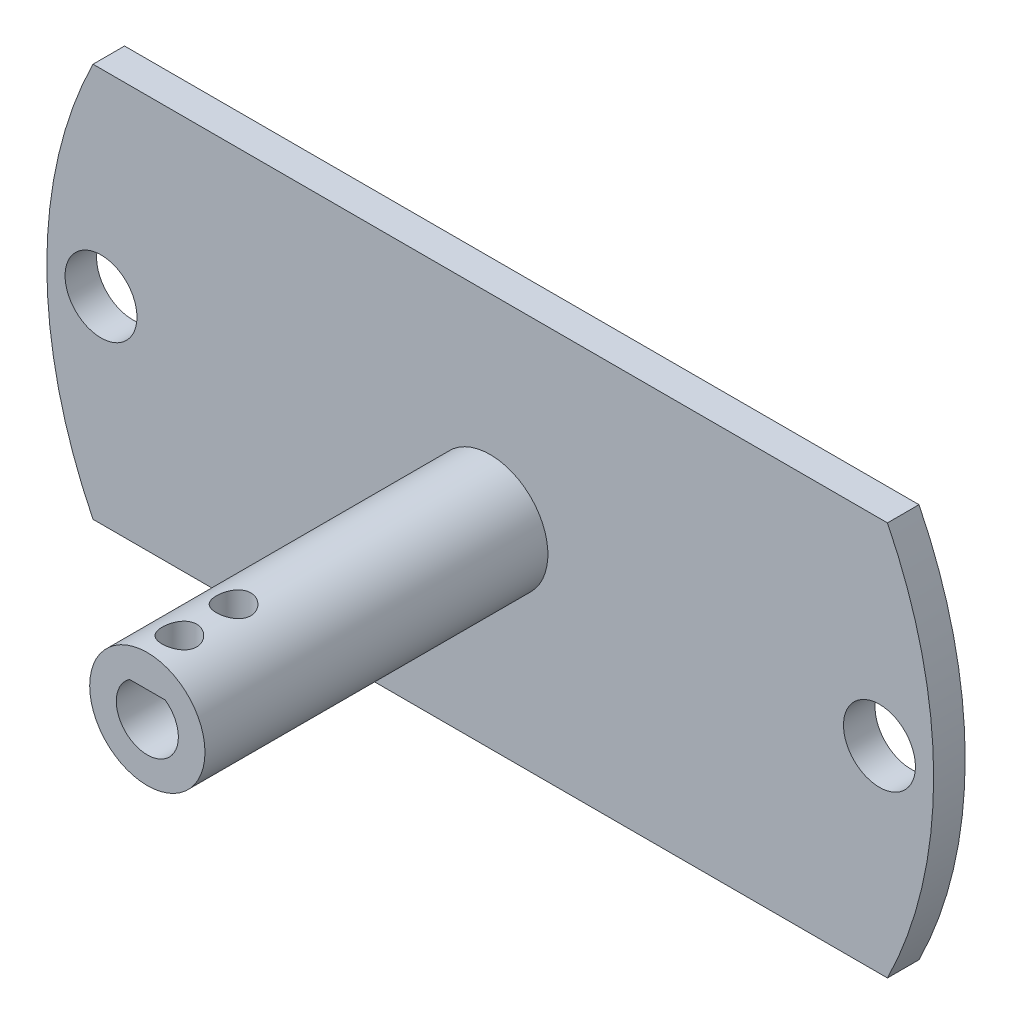
SolidWorks part; units mm, degrees
ref_plane "Alzado" through (0, 0, 0) normal (0, 0, 1) x (1, 0, 0)
ref_plane "Planta" through (0, 0, 0) normal (0, 1, 0) x (1, 0, 0)
ref_plane "Vista lateral" through (0, 0, 0) normal (1, 0, 0) x (0, 0, -1)
sketch "Croquis1" plane through (0, 0, 0) normal (0, 0, 1) x (1, 0, 0)
  line L0 (0, 0) -> (0, 2.5851) construction
  line L7 (-1.8, 2.5851) -> (1.8, 2.5851)
  circle A0 centre (0, 0) radius 5.85
  arc A1 (-1.8, 2.5851) -> (1.8, 2.5851) centre (0, 0) ccw
  point P14 (0, 2.5851)
  dimension "D2" = 6.3
  dimension "D1" = 11.7
  dimension "D3" = 3.6
extrude "Saliente-Extruir1" add sketch "Croquis1" along normal blind 38
sketch "Croquis2" plane through (0, 2.5851, 0) normal (0, 1, 0) x (1, 0, 0)
  line L0 (0, -38) -> (0, -34.75) construction
  line L2 (0, -34.75) -> (0, -33) construction
  line L3 (0, -33) -> (0, -31) construction
  line L4 (0, -31) -> (0, -29.25) construction
  line L5 (0, -29.25) -> (0, -26) construction
  line L6 (-5.85, -38) -> (5.85, -38) construction
  circle A0 centre (0, -34.75) radius 1.75
  circle A1 centre (0, -29.25) radius 1.75
  point P2 (0, 0)
  point P9 (0, 0)
  point P12 (0, 0)
  dimension "D1" = 3.5
  dimension "D2" = 12
  dimension "D3" = 2
extrude "Cortar-Extruir1" cut sketch "Croquis2" along normal blind 7.5
sketch "Croquis3" plane through (0, 0, 0) normal (0, 0, -1) x (-1, 0, 0)
  circle A0 centre (0, 0) radius 45
  point P3 (0, 0)
  dimension "D1" = 90
extrude "Saliente-Extruir2" add sketch "Croquis3" against normal blind 3.2
sketch "Croquis5" plane through (0, 0, 0) normal (0, 0, -1) x (-1, 0, 0)
  line L0 (0, 0) -> (0, 7.5) construction
  line L1 (0, 7.5) -> (-7.5, 7.5) construction
  line L2 (0, 0) -> (-34, 0) construction
  line L3 (-34, 0) -> (-45, 0) construction
  line L4 (0, 7.5) -> (0, 20) construction
  line L5 (0, 20) -> (-75, 20)
  line L6 (-75, 20) -> (-75, 50)
  line L7 (-75, 50) -> (75, 50)
  line L8 (75, 50) -> (75, 20)
  line L9 (75, 20) -> (0, 20)
  line L10 (75, -50) -> (75, -20)
  line L11 (-75, -50) -> (75, -50)
  line L12 (-75, -20) -> (-75, -50)
  line L13 (0, -20) -> (-75, -20)
  line L14 (75, -20) -> (0, -20)
  circle A4 centre (0, 0) radius 45 construction
  circle A5 centre (-39.5, 0) radius 3.65
  circle A6 centre (39.5, 0) radius 3.65
  point P14 (0.2713, -0.2713)
  dimension "D3" = 45
  dimension "D5" = 7.3
  dimension "D1" = 7.5
  dimension "D2" = 7.5
  dimension "D4" = 34
  dimension "D6" = 20
  dimension "D7" = 30
  dimension "D8" = 150
extrude "Cortar-Extruir2" cut sketch "Croquis5" against normal blind 5 and the other way through all
